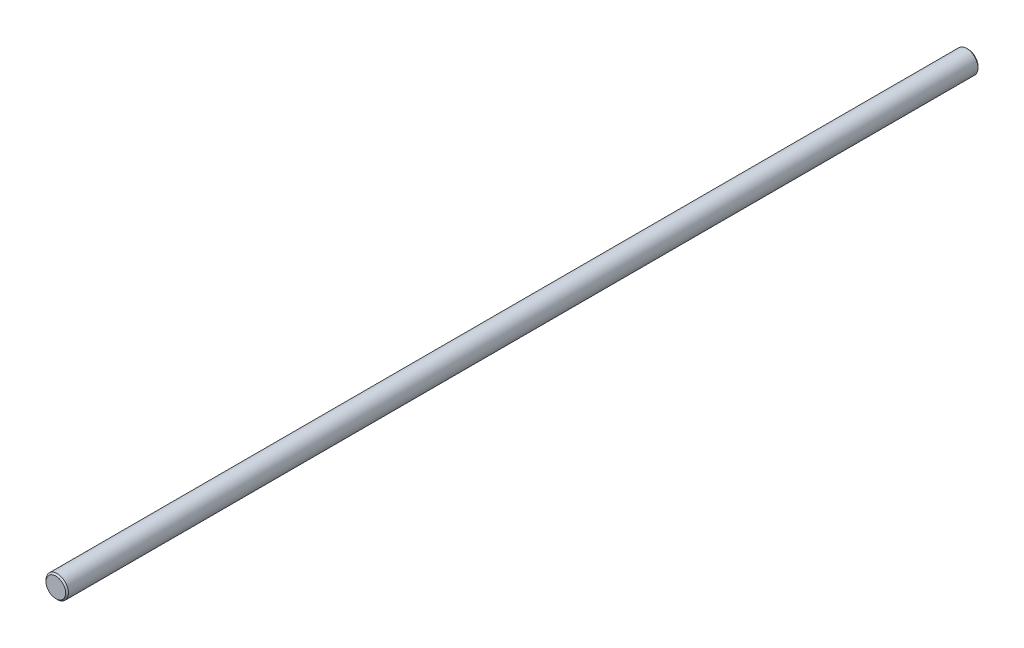
SolidWorks part; units mm, degrees
material "Хромистая нержавеющая сталь"
ref_plane "Спереди" through (0, 0, 0) normal (0, 0, 1) x (1, 0, 0)
ref_plane "Сверху" through (0, 0, 0) normal (0, 1, 0) x (1, 0, 0)
ref_plane "Справа" through (0, 0, 0) normal (1, 0, 0) x (0, 0, -1)
sketch "Эскиз1" plane through (0, 0, 0) normal (0, 0, 1) x (1, 0, 0)
  circle A0 centre (0, 0) radius 8
  dimension "D1" = 16
extrude "Бобышка-Вытянуть1" add sketch "Эскиз1" along normal blind 650
chamfer "Фаска1" distance 1 angle 45 2 edges at (8, 0, 650) (8, 0, 0)
